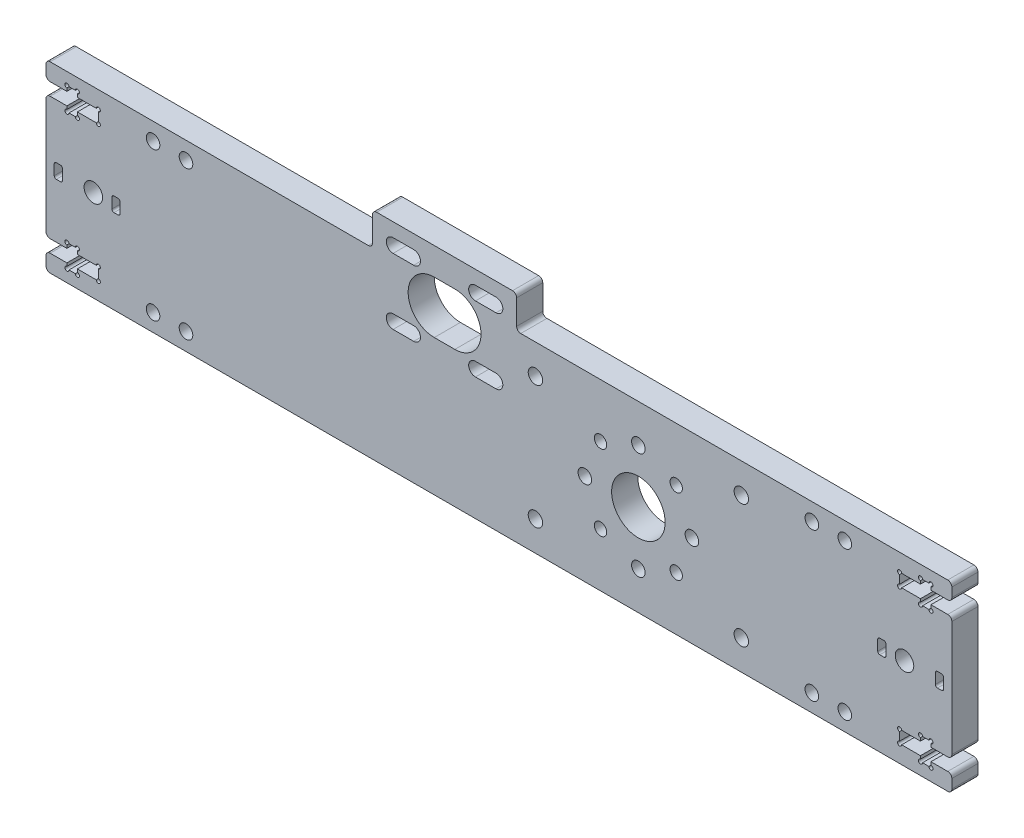
SolidWorks part; units mm, degrees
material "Acrylic (Medium-high impact)"
ref_plane "Front Plane" through (0, 0, 0) normal (0, 0, 1) x (1, 0, 0)
ref_plane "Top Plane" through (0, 0, 0) normal (0, 1, 0) x (1, 0, 0)
ref_plane "Right Plane" through (0, 0, 0) normal (1, 0, 0) x (0, 0, -1)
sketch "Sketch1" plane through (0, 0, 0) normal (0, 0, 1) x (1, 0, 0)
  line L0 (0, 22.225) -> (220, 22.225) construction
  line L1 (0, 0) -> (220, 0)
  line L2 (0, 0) -> (0, 44.45)
  line L3 (0, 44.45) -> (220, 44.45)
  line L4 (220, 0) -> (220, 44.45)
  line L5 (110, 44.45) -> (110, 0) construction
  line L6 (5.08, 8.4772) -> (7.62, 8.4772)
  line L7 (0, 5.715) -> (12.7, 5.715) construction
  line L8 (0, 5.715) -> (0, 4.191)
  line L9 (0, 4.191) -> (12.7, 4.191)
  line L10 (12.7, 7.239) -> (12.7, 4.191)
  line L11 (5.08, 5.715) -> (7.62, 5.715) construction
  line L12 (5.08, 8.4772) -> (5.08, 2.9527)
  line L13 (5.08, 2.9527) -> (7.62, 2.9527)
  line L14 (7.62, 8.4772) -> (7.62, 2.9527)
  line L15 (0, 7.239) -> (12.7, 7.239)
  line L16 (0, 38.735) -> (12.7, 38.735) construction
  line L17 (5.08, 41.4973) -> (7.62, 41.4973)
  line L18 (0, 40.259) -> (12.7, 40.259)
  line L19 (12.7, 37.211) -> (12.7, 40.259)
  line L20 (7.62, 35.9728) -> (7.62, 41.4973)
  line L21 (0, 37.211) -> (12.7, 37.211)
  line L22 (5.08, 35.9727) -> (5.08, 41.4973)
  line L23 (5.08, 35.9727) -> (7.62, 35.9728)
  line L24 (214.92, 35.9728) -> (212.38, 35.9728)
  line L25 (214.92, 2.9527) -> (212.38, 2.9527)
  line L26 (214.92, 8.4772) -> (212.38, 8.4772)
  line L27 (214.92, 8.4772) -> (214.92, 2.9527)
  line L28 (212.38, 8.4772) -> (212.38, 2.9527)
  line L29 (220, 5.715) -> (207.3, 5.715) construction
  line L30 (207.3, 7.239) -> (207.3, 4.191)
  line L31 (220, 4.191) -> (207.3, 4.191)
  line L32 (220, 7.239) -> (207.3, 7.239)
  line L33 (220, 38.735) -> (207.3, 38.735) construction
  line L34 (220, 37.211) -> (207.3, 37.211)
  line L35 (207.3, 37.211) -> (207.3, 40.259)
  line L36 (220, 40.259) -> (207.3, 40.259)
  line L37 (214.92, 35.9728) -> (214.92, 41.4973)
  line L38 (212.38, 35.9728) -> (212.38, 41.4973)
  line L39 (214.92, 41.4973) -> (212.38, 41.4973)
  point P9 (0, 5.715)
  dimension "D1" = 44.45
  dimension "D2" = 220
  dimension "D3" = 16.51
  dimension "D4" = 5.5245
  dimension "D5" = 12.7
  dimension "D6" = 3.048
  dimension "D7" = 2.54
  dimension "D8" = 5.08
extrude "Boss-Extrude1" add sketch "Sketch1" along normal blind 6.35 contours L2 L15 L12 L6 L14 L10 L9 L13 L1 L4 L3
sketch "Sketch2" plane through (0, 0, 6.35) normal (0, 0, 1) x (1, 0, 0)
  line L0 (30, 44.45) -> (30, 0) construction
  line L1 (0, 44.45) -> (220, 44.45) construction
  line L2 (0, 0) -> (220, 0) construction
  line L3 (0, 7.239) -> (0, 37.211) construction
  line L4 (30, 22.225) -> (0, 22.225) construction
  line L5 (0, 7.239) -> (0, 37.211) construction
  line L6 (186, 40.225) -> (194, 4.225) construction
  line L7 (190, 22.225) -> (220, 22.225) construction
  line L8 (220, 7.239) -> (220, 37.211) construction
  circle A0 centre (26, 40.225) radius 1.65
  circle A1 centre (34, 40.225) radius 1.65
  circle A2 centre (34, 4.225) radius 1.65
  circle A3 centre (26, 4.225) radius 1.65
  circle A4 centre (186, 40.225) radius 1.65
  circle A5 centre (194, 40.225) radius 1.65
  circle A6 centre (194, 4.225) radius 1.65
  circle A7 centre (186, 4.225) radius 1.65
  point P6 (0, 22.225)
  dimension "D2" = 3.3
  dimension "D3" = 4
  dimension "D4" = 18
  dimension "D1" = 30
  dimension "D6" = 30
  dimension "D5" = 2
extrude "Cut-Extrude1" cut sketch "Sketch2" against normal through all
sketch "Sketch3" plane through (0, 0, 6.35) normal (0, 0, 1) x (1, 0, 0)
  line L0 (0, 22.225) -> (143.8653, 22.225) construction
  line L1 (0, 7.239) -> (0, 37.211) construction
  line L2 (143.8653, 22.225) -> (143.8653, 35.225) construction
  line L3 (153.0577, 31.4174) -> (143.8653, 22.225) construction
  circle A0 centre (143.8653, 22.225) radius 6.5
  circle A1 centre (143.8653, 35.225) radius 1.65
  circle A2 centre (156.8653, 22.225) radius 1.65
  circle A3 centre (143.8653, 9.225) radius 1.65
  circle A4 centre (130.8653, 22.225) radius 1.65
  circle A5 centre (153.0577, 31.4174) radius 1.5
  circle A6 centre (143.8653, 22.225) radius 13 construction
  circle A7 centre (153.0577, 13.0326) radius 1.5
  circle A8 centre (134.6729, 13.0326) radius 1.5
  circle A9 centre (134.6729, 31.4174) radius 1.5
  point P16 (143.8653, 22.225)
  point P26 (143.8653, 22.225)
  dimension "D2" = 13
  dimension "D3" = 3.3
  dimension "D4" = 13
  dimension "D7" = 3
  dimension "D1" = 143.8653
  dimension "D6" = 135
  dimension "D5" = 4
  dimension "D8" = 4
extrude "Cut-Extrude2" cut sketch "Sketch3" against normal through all
sketch "Sketch6" plane through (0, 0, 6.35) normal (0, 0, 1) x (1, 0, 0)
  line L0 (111.7978, 44.45) -> (111.7978, 0) construction
  line L1 (0, 44.45) -> (220, 44.45) construction
  line L2 (81.7978, 44.45) -> (81.7978, 0) construction
  line L3 (81.7978, 0) -> (111.7978, 0) construction
  line L4 (96.7978, 0) -> (96.7978, 44.45) construction
  line L6 (81.7978, 22.225) -> (111.7978, 22.225) construction
  line L8 (96.7978, 39.45) -> (143.8653, 22.225) construction
  line L9 (0, 0) -> (220, 0) construction
  line L11 (97.5392, 44.4958) -> (146.0894, 37.3625) construction
  line L13 (94.1071, 35.1176) -> (135.7931, 9.2277) construction
  circle A1 centre (96.7978, 39.45) radius 6.35
  arc A6 (135.7931, 9.2277) -> (146.0894, 37.3625) centre (143.8653, 22.225) ccw construction
  arc A7 (97.5392, 44.4958) -> (94.1071, 35.1176) centre (96.7978, 39.45) ccw construction
  dimension "D5" = 5
  dimension "D6" = 50.1204
  dimension "D3" = 12.7
  dimension "D8" = 30.6
  dimension "D9" = 10.2
  dimension "D1" = 30
extrude "Cut-Extrude3" cut sketch "Sketch6" against normal through all
sketch "Sketch8" plane through (0, 0, 6.35) normal (0, 0, 1) x (1, 0, 0)
  line L0 (79.2978, 39.45) -> (96.7978, 39.45) construction
  line L1 (79.2978, 52.45) -> (114.2978, 52.45)
  line L2 (79.2978, 52.45) -> (79.2978, 26.45)
  line L3 (79.2978, 26.45) -> (114.2978, 26.45)
  line L4 (114.2978, 52.45) -> (114.2978, 26.45)
  line L5 (96.7978, 39.45) -> (114.2978, 39.45) construction
  circle A0 centre (96.7978, 39.45) radius 6.35
  arc A1 (92.8834, 44.45) -> (100.7122, 44.45) centre (96.7978, 39.45) ccw construction
  dimension "D1" = 35
  dimension "D2" = 26
extrude "Boss-Extrude2" add sketch "Sketch8" against normal through all
sketch "Sketch10" plane through (0, 0, 6.35) normal (0, 0, 1) x (1, 0, 0)
  line L0 (86.7978, 47.45) -> (86.7978, 31.45) construction
  line L1 (86.7978, 31.45) -> (106.7978, 31.45) construction
  line L2 (106.7978, 31.45) -> (106.7978, 47.45) construction
  line L3 (106.7978, 47.45) -> (86.7978, 47.45) construction
  line L4 (86.7978, 47.45) -> (96.7978, 39.45) construction
  line L5 (96.7978, 39.45) -> (106.7978, 31.45) construction
  line L6 (84.2978, 31.45) -> (89.2978, 31.45) construction
  line L7 (84.2978, 33.1) -> (89.2978, 33.1)
  line L8 (84.2978, 29.8) -> (89.2978, 29.8)
  line L9 (104.2978, 31.45) -> (109.2978, 31.45) construction
  line L10 (104.2978, 33.1) -> (109.2978, 33.1)
  line L11 (104.2978, 29.8) -> (109.2978, 29.8)
  line L12 (84.2978, 47.45) -> (89.2978, 47.45) construction
  line L13 (84.2978, 49.1) -> (89.2978, 49.1)
  line L14 (84.2978, 45.8) -> (89.2978, 45.8)
  line L15 (104.2978, 47.45) -> (109.2978, 47.45) construction
  line L16 (104.2978, 49.1) -> (109.2978, 49.1)
  line L17 (104.2978, 45.8) -> (109.2978, 45.8)
  line L18 (94.2978, 39.45) -> (99.2978, 39.45) construction
  line L19 (94.2978, 45.8) -> (99.2978, 45.8)
  line L20 (94.2978, 33.1) -> (99.2978, 33.1)
  arc A0 (84.2978, 33.1) -> (84.2978, 29.8) centre (84.2978, 31.45) ccw
  arc A1 (89.2978, 29.8) -> (89.2978, 33.1) centre (89.2978, 31.45) ccw
  arc A2 (104.2978, 33.1) -> (104.2978, 29.8) centre (104.2978, 31.45) ccw
  arc A3 (109.2978, 29.8) -> (109.2978, 33.1) centre (109.2978, 31.45) ccw
  arc A4 (84.2978, 49.1) -> (84.2978, 45.8) centre (84.2978, 47.45) ccw
  arc A5 (89.2978, 45.8) -> (89.2978, 49.1) centre (89.2978, 47.45) ccw
  arc A6 (104.2978, 49.1) -> (104.2978, 45.8) centre (104.2978, 47.45) ccw
  arc A7 (109.2978, 45.8) -> (109.2978, 49.1) centre (109.2978, 47.45) ccw
  arc A8 (94.2978, 45.8) -> (94.2978, 33.1) centre (94.2978, 39.45) ccw
  arc A9 (99.2978, 33.1) -> (99.2978, 45.8) centre (99.2978, 39.45) ccw
  circle A10 centre (96.7978, 39.45) radius 6.35 construction
  point P5 (86.7978, 31.45)
  point P17 (106.7978, 31.45)
  point P23 (86.7978, 47.45)
  point P30 (106.7978, 47.45)
  point P36 (96.7978, 39.45)
  dimension "D1" = 5
  dimension "D4" = 1.65
  dimension "D2" = 16
  dimension "D3" = 20
  dimension "D7" = 5
  dimension "D5" = 2
  dimension "D6" = 2
extrude "Cut-Extrude5" cut sketch "Sketch10" against normal through all
fillet "Fillet1" radius 1 16 edges at (0, 0, 3.175) (0, 4.191, 3.175) (0, 7.239, 3.175) (0, 37.211, 3.175) (0, 40.259, 3.175) (220, 40.259, 3.175) (220, 7.239, 3.175) (220, 0, 3.175) (220, 4.191, 3.175) (220, 37.211, 3.175) (220, 44.45, 3.175) (0, 44.45, 3.175) (114.2978, 44.45, 3.175) (79.2978, 44.45, 3.175) (114.2978, 52.45, 3.175) (79.2978, 52.45, 3.175)
sketch "Sketch7" plane through (0, 0, 6.35) normal (0, 0, 1) x (1, 0, 0)
  line L0 (220, 22.225) -> (0, 22.225) construction
  line L1 (220, 8.239) -> (220, 36.211) construction
  line L2 (0, 8.239) -> (0, 36.211) construction
  line L4 (115.2978, 44.45) -> (219, 44.45) construction
  line L5 (110, 44.45) -> (110, 0) construction
  line L6 (1, 0) -> (219, 0) construction
  circle A0 centre (207.3, 40.259) radius 0.5
  circle A1 centre (207.3, 37.211) radius 0.5
  circle A2 centre (212.38, 35.9728) radius 0.5
  circle A3 centre (214.92, 35.9728) radius 0.5
  circle A4 centre (212.38, 41.4973) radius 0.5
  circle A5 centre (214.92, 41.4973) radius 0.5
  circle A6 centre (214.92, 2.9527) radius 0.5
  circle A7 centre (212.38, 2.9527) radius 0.5
  circle A8 centre (214.92, 8.4772) radius 0.5
  circle A9 centre (212.38, 8.4772) radius 0.5
  circle A10 centre (207.3, 7.239) radius 0.5
  circle A11 centre (207.3, 4.191) radius 0.5
  circle A12 centre (12.7, 4.191) radius 0.5
  circle A13 centre (12.7, 7.239) radius 0.5
  circle A14 centre (7.62, 8.4772) radius 0.5
  circle A15 centre (5.08, 8.4772) radius 0.5
  circle A16 centre (7.62, 2.9527) radius 0.5
  circle A17 centre (5.08, 2.9527) radius 0.5
  circle A18 centre (5.08, 41.4973) radius 0.5
  circle A19 centre (7.62, 41.4973) radius 0.5
  circle A20 centre (5.08, 35.9728) radius 0.5
  circle A21 centre (7.62, 35.9728) radius 0.5
  circle A22 centre (12.7, 37.211) radius 0.5
  circle A23 centre (12.7, 40.259) radius 0.5
  dimension "D1" = 1
extrude "Cut-Extrude4" cut sketch "Sketch7" against normal through all
sketch "Sketch11" plane through (0, 0, 6.35) normal (0, 0, 1) x (1, 0, 0)
  line L0 (0, 22.225) -> (2, 22.225) construction
  line L1 (2, 23.975) -> (4, 23.975)
  line L2 (2, 23.975) -> (2, 20.475)
  line L3 (2, 20.475) -> (4, 20.475)
  line L4 (18, 23.975) -> (18, 20.475)
  line L5 (0, 8.239) -> (0, 36.211) construction
  line L6 (202, 23.975) -> (204, 23.975)
  line L7 (202, 23.975) -> (202, 20.475)
  line L8 (202, 20.475) -> (204, 20.475)
  line L9 (218, 23.975) -> (218, 20.475)
  line L10 (3, 23.975) -> (17, 23.975) construction
  line L11 (4, 23.975) -> (4, 20.475)
  line L12 (16, 23.975) -> (18, 23.975)
  line L13 (16, 23.975) -> (16, 20.475)
  line L14 (16, 20.475) -> (18, 20.475)
  line L15 (204, 23.975) -> (204, 20.475)
  line L16 (216, 23.975) -> (218, 23.975)
  line L17 (216, 23.975) -> (216, 20.475)
  line L18 (216, 20.475) -> (218, 20.475)
  line L19 (18, 22.225) -> (202, 22.225) construction
  line L20 (220, 8.239) -> (220, 36.211) construction
  line L21 (204, 22.225) -> (216, 22.225) construction
  line L22 (4, 22.225) -> (11.5, 22.225) construction
  circle A0 centre (208.5, 22.225) radius 2.25
  circle A1 centre (11.5, 22.225) radius 2.25
  dimension "D7" = 4.5
  dimension "D8" = 11.5
  dimension "D1" = 3.5
  dimension "D2" = 14
  dimension "D3" = 2
  dimension "D5" = 2
  dimension "D6" = 2
  dimension "D9" = 11.5
  dimension "D4" = 2
extrude "Cut-Extrude6" cut sketch "Sketch11" against normal through all
fillet "Fillet2" radius 0.5 16 edges at (18, 23.975, 3.175) (18, 20.475, 3.175) (16, 20.475, 3.175) (16, 23.975, 3.175) (2, 23.975, 3.175) (4, 23.975, 3.175) (4, 20.475, 3.175) (2, 20.475, 3.175) (202, 20.475, 3.175) (204, 23.975, 3.175) (202, 23.975, 3.175) (204, 20.475, 3.175) (218, 20.475, 3.175) (216, 20.475, 3.175) (216, 23.975, 3.175) (218, 23.975, 3.175)
sketch "Sketch12" plane through (0, 0, 6.35) normal (0, 0, 1) x (1, 0, 0)
  line L0 (143.8653, 37.225) -> (143.8653, 22.225) construction
  line L1 (118.8653, 37.225) -> (168.8653, 37.225) construction
  line L2 (118.8653, 37.225) -> (118.8653, 7.225) construction
  line L3 (118.8653, 7.225) -> (168.8653, 7.225) construction
  line L4 (168.8653, 37.225) -> (168.8653, 7.225) construction
  line L5 (143.8653, 22.225) -> (143.8653, 7.225) construction
  circle A0 centre (118.8653, 37.225) radius 1.75
  circle A1 centre (118.8653, 7.225) radius 1.75
  circle A2 centre (168.8653, 7.225) radius 1.75
  circle A3 centre (168.8653, 37.225) radius 1.75
  dimension "D1" = 3.5
  dimension "D2" = 30
  dimension "D3" = 50
extrude "Cut-Extrude7" cut sketch "Sketch12" against normal through all
